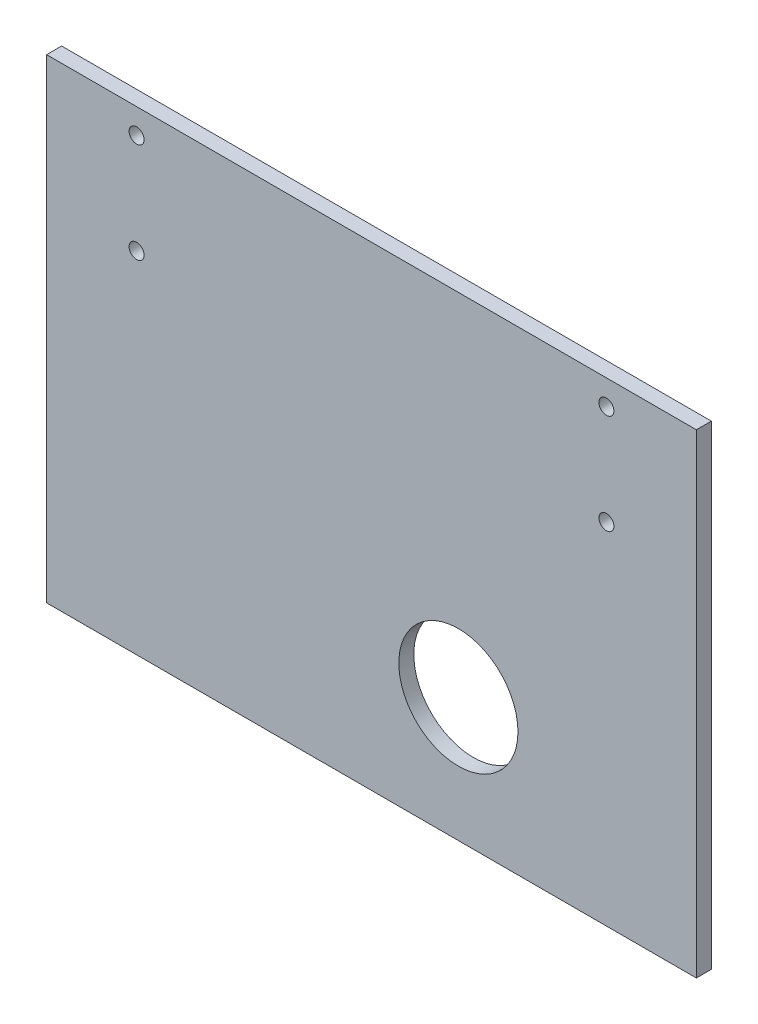
SolidWorks part; units mm, degrees
ref_plane "前视基准面" through (0, 0, 0) normal (0, 0, 1) x (1, 0, 0)
ref_plane "上视基准面" through (0, 0, 0) normal (0, 1, 0) x (1, 0, 0)
ref_plane "右视基准面" through (0, 0, 0) normal (1, 0, 0) x (0, 0, -1)
sketch "草图1" plane through (0, 0, 0) normal (0, 0, 1) x (1, 0, 0)
  line L1 (65, -47.5) -> (-65, -47.5)
  line L2 (65, -47.5) -> (65, 47.5)
  line L3 (65, 47.5) -> (-65, 47.5)
  line L4 (-65, -47.5) -> (-65, 47.5)
  line L5 (65, -47.5) -> (-65, 47.5) construction
  line L6 (65, 47.5) -> (-65, -47.5) construction
  point P0 (0, 0)
  dimension "D1" = 130
  dimension "D2" = 95
extrude "凸台-拉伸1" add sketch "草图1" along normal blind 3
sketch "草图2" plane through (0, 0, 3) normal (0, 0, 1) x (1, 0, 0)
  circle A0 centre (-47, 42.5) radius 1.5
  circle A1 centre (-47, 22.5) radius 1.5
  circle A2 centre (47, 42.5) radius 1.5
  circle A3 centre (47, 22.5) radius 1.5
  circle A4 centre (17.3827, -22.6774) radius 11.9222
extrude "切除-拉伸1" cut sketch "草图2" against normal blind 4
